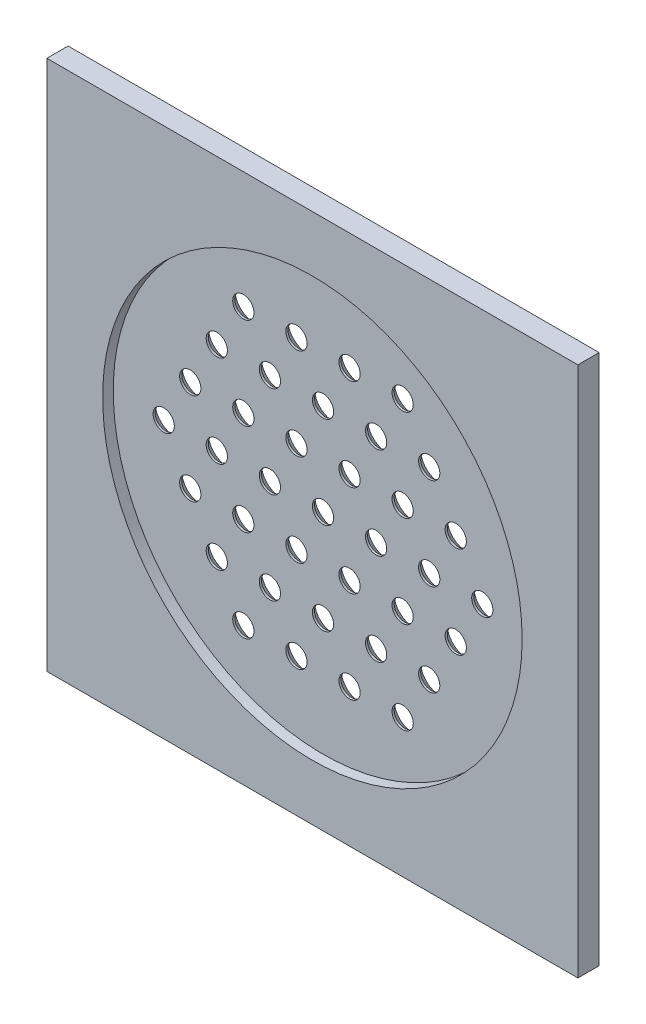
SolidWorks part; units mm, degrees
material "Сосна"
ref_plane "Front" through (0, 0, 0) normal (0, 0, 1) x (1, 0, 0)
ref_plane "Top" through (0, 0, 0) normal (0, 1, 0) x (1, 0, 0)
ref_plane "Right" through (0, 0, 0) normal (1, 0, 0) x (0, 0, -1)
sketch "Эскиз1" plane through (0, 66.7543, 0) normal (0, 0, 1) x (-1, 0, 0)
  line L36 (0, 66.7543) -> (50, 66.7543)
  line L37 (0, 66.7543) -> (0, 16.7543)
  line L38 (0, 16.7543) -> (50, 16.7543)
  line L39 (50, 66.7543) -> (50, 16.7543)
  dimension "D1" = 50
  dimension "D2" = 50
extrude "Бобышка-Вытянуть1" add sketch "Эскиз1" along normal blind 2
sketch "Эскиз2" plane through (0, 0, 2) normal (0, 0, 1) x (1, 0, 0)
  line L0 (-20, 16.3397) -> (-30, 16.3397) construction
  line L1 (-32.5, 12.0096) -> (-27.5, 12.0096) construction
  line L2 (-27.5, 12.0096) -> (-22.5, 12.0096) construction
  line L4 (-17.5, 12.0096) -> (-22.5, 12.0096) construction
  circle A1 centre (-25, 25) radius 1
  circle A2 centre (-20, 25) radius 1
  circle A3 centre (-15, 25) radius 1
  circle A4 centre (-10, 25) radius 1
  circle A5 centre (-22.5, 20.6699) radius 1
  circle A6 centre (-20, 16.3397) radius 1
  circle A7 centre (-17.5, 12.0096) radius 1
  circle A8 centre (-27.5, 20.6699) radius 1
  circle A9 centre (-30, 16.3397) radius 1
  circle A10 centre (-32.5, 12.0096) radius 1
  circle A11 centre (-30, 25) radius 1
  circle A12 centre (-35, 25) radius 1
  circle A13 centre (-40, 25) radius 1
  circle A14 centre (-27.5, 29.3301) radius 1
  circle A15 centre (-30, 33.6603) radius 1
  circle A16 centre (-32.5, 37.9904) radius 1
  circle A17 centre (-22.5, 29.3301) radius 1
  circle A18 centre (-20, 33.6603) radius 1
  circle A19 centre (-17.5, 37.9904) radius 1
  circle A20 centre (-25, 16.3397) radius 1
  circle A21 centre (-27.5, 12.0096) radius 1
  circle A22 centre (-22.5, 12.0096) radius 1
  circle A23 centre (-32.5, 20.6699) radius 1
  circle A24 centre (-37.5, 20.6699) radius 1
  circle A25 centre (-35, 16.3397) radius 1
  circle A26 centre (-32.5, 29.3301) radius 1
  circle A27 centre (-35, 33.6603) radius 1
  circle A28 centre (-37.5, 29.3301) radius 1
  circle A29 centre (-25, 33.6603) radius 1
  circle A30 centre (-22.5, 37.9904) radius 1
  circle A31 centre (-27.5, 37.9904) radius 1
  circle A32 centre (-17.5, 29.3301) radius 1
  circle A33 centre (-12.5, 29.3301) radius 1
  circle A34 centre (-15, 33.6603) radius 1
  circle A35 centre (-17.5, 20.6699) radius 1
  circle A36 centre (-15, 16.3397) radius 1
  circle A37 centre (-12.5, 20.6699) radius 1
  point P42 (-25, 25)
  point P80 (-25, 25)
  point P92 (-25, 16.3397)
  dimension "D1" = 4
  dimension "D6" = 2
  dimension "D10" = 5
  dimension "D3" = 3
  dimension "D7" = 25
  dimension "D8" = 25
  dimension "D9" = 10
  dimension "D4" = 2
  dimension "D2" = 6
  dimension "D5" = 6
extrude "Отверстия для динамика" cut sketch "Эскиз2" against normal through all
sketch "Эскиз3" plane through (0, 0, 2) normal (0, 0, 1) x (1, 0, 0)
  circle A0 centre (-25, 25) radius 19.75
  dimension "D1" = 39.5
extrude "Вырез под динамик" cut sketch "Эскиз3" against normal blind 1
chamfer "Фаска1" distance 0.8 angle 45 37 edges at (-14, 16.3397, 0) (-9, 25, 0) (-11.5, 20.6699, 0) (-16.5, 12.0096, 0) (-21.5, 12.0096, 0) (-19, 16.3397, 0) (-16.5, 20.6699, 0) (-14, 25, 0) (-11.5, 29.3301, 0) (-14, 33.6603, 0) (-16.5, 29.3301, 0) (-19, 25, 0) (-21.5, 20.6699, 0) (-26.5, 12.0096, 0) (-24, 16.3397, 0) (-26.5, 20.6699, 0) (-31.5, 12.0096, 0) (-29, 16.3397, 0) (-34, 16.3397, 0) (-31.5, 20.6699, 0) (-36.5, 20.6699, 0) (-19, 33.6603, 0) (-21.5, 29.3301, 0) (-24, 25, 0) (-26.5, 29.3301, 0) (-29, 25, 0) (-31.5, 29.3301, 0) (-34, 25, 0) (-39, 25, 0) (-36.5, 29.3301, 0) (-29, 33.6603, 0) (-34, 33.6603, 0) (-31.5, 37.9904, 0) (-26.5, 37.9904, 0) (-24, 33.6603, 0) (-21.5, 37.9904, 0) (-16.5, 37.9904, 0)
